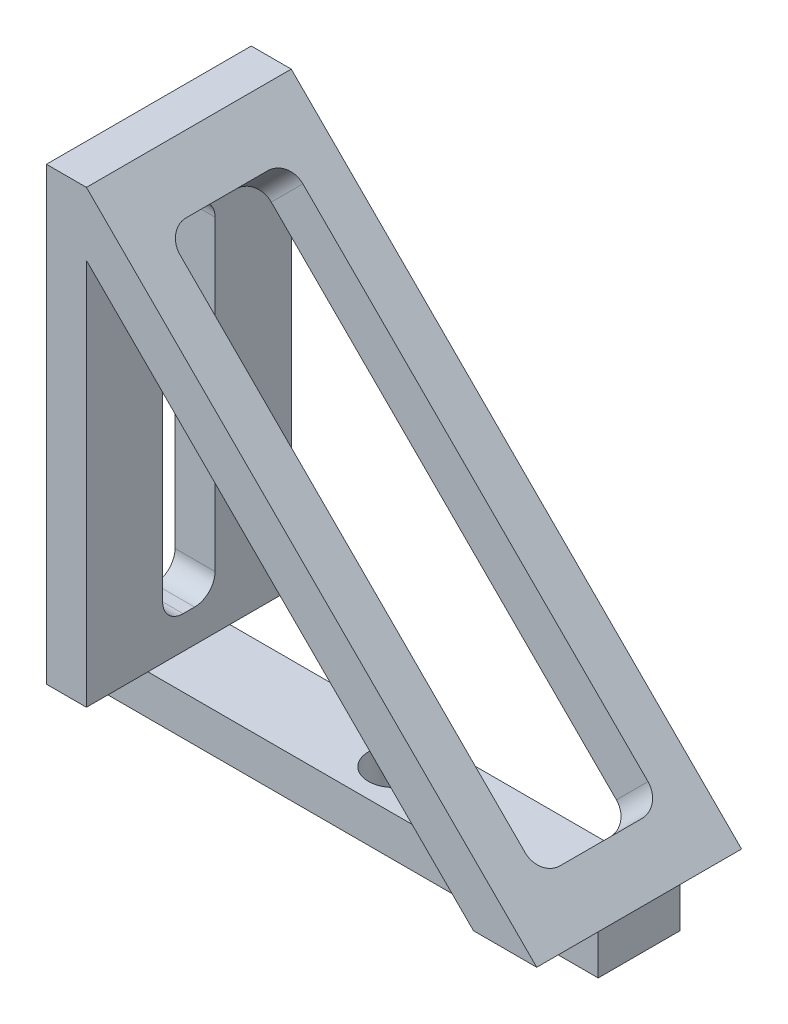
SolidWorks part; units mm, degrees
ref_plane "Front" through (0, 0, 0) normal (0, 0, 1) x (1, 0, 0)
ref_plane "Top" through (0, 0, 0) normal (0, 1, 0) x (1, 0, 0)
ref_plane "Right" through (0, 0, 0) normal (1, 0, 0) x (0, 0, -1)
sketch "Sketch1" plane through (0, 0, 0) normal (0, 0, 1) x (1, 0, 0)
  line L3 (-6.2, 69.8) -> (-6.2, -6.2)
  line L4 (-6.2, -6.2) -> (69.8, -6.2)
  line L6 (-6.2, 69.8) -> (0, 69.8)
  line L7 (0, 69.8) -> (69.8, 0)
  line L8 (50, 0) -> (-50, 0) construction
  line L9 (69.8, 0) -> (69.8, -6.2)
  line L10 (0, 60) -> (60, 0)
  line L11 (60, 0) -> (0, 0)
  line L12 (0, 0) -> (0, 60)
  dimension "D1" = 76
  dimension "D2" = 76
  dimension "D3" = 6.2
  dimension "D4" = 6.2
  dimension "D5" = 60
extrude "Boss-Extrude1" add sketch "Sketch1" along normal mid plane 31.75
sketch "Sketch2" plane through (34.9, 34.9, 0) normal (0.7071, 0.7071, 0) x (0, 0, -1)
  line L0 (0, 50) -> (0, -50) construction
  line L1 (-9.525, -41) -> (9.525, -41)
  line L2 (-9.525, -41) -> (-9.525, 41)
  line L3 (-9.525, 41) -> (9.525, 41)
  line L4 (9.525, -41) -> (9.525, 41)
  line L5 (-9.525, -41) -> (9.525, 41) construction
  line L6 (-9.525, 41) -> (9.525, -41) construction
  point P0 (0, 0)
  point P5 (9.525, 0)
  point P9 (0, 41)
  dimension "D1" = 82
  dimension "D2" = 19.05
extrude "Cut-Extrude1" cut sketch "Sketch2" against normal up to next
sketch "Sketch3" plane through (0, 0, 0) normal (1, 0, 0) x (0, 0, -1)
  line L0 (0, 50) -> (0, -50) construction
  line L1 (-4.064, 5.08) -> (4.064, 5.08)
  line L2 (-4.064, 5.08) -> (-4.064, 59)
  line L3 (-4.064, 59) -> (4.064, 59)
  line L4 (4.064, 5.08) -> (4.064, 59)
  line L5 (-4.064, 5.08) -> (4.064, 59) construction
  line L6 (-4.064, 59) -> (4.064, 5.08) construction
  line L7 (-15.875, 0) -> (15.875, 0) construction
  line L8 (-15.875, 60) -> (15.875, 60) construction
  point P0 (0, 32.04)
  point P5 (0, 59)
  point P12 (4.064, 59)
  dimension "D1" = 8.128
  dimension "D2" = 5.08
  dimension "D3" = 1
extrude "Cut-Extrude2" cut sketch "Sketch3" against normal up to next
sketch "Sketch4" plane through (69.8, 0, 0) normal (1, 0, 0) x (0, 0, -1)
  line L0 (50, 0) -> (-50, 0) construction
  line L1 (-15.875, -6.2) -> (-6.35, -6.2)
  line L2 (-15.875, -6.2) -> (-15.875, 0)
  line L3 (-15.875, 0) -> (-6.35, 0)
  line L4 (-6.35, -6.2) -> (-6.35, 0)
  line L6 (15.875, -6.2) -> (6.35, -6.2)
  line L7 (15.875, -6.2) -> (15.875, 0)
  line L8 (15.875, 0) -> (6.35, 0)
  line L9 (6.35, -6.2) -> (6.35, 0)
  dimension "D1" = 12.7
extrude "Cut-Extrude3" cut sketch "Sketch4" against normal up to next
sketch "Sketch5" plane through (0, -6.2, 0) normal (0, -1, 0) x (1, 0, 0)
  line L0 (50, 0) -> (-50, 0) construction
  line L1 (-6.2, 6.35) -> (69.8, 6.35) construction
  point P0 (31.8, 0)
  point P5 (31.8, 6.35)
hole_wizard "5/16 (0.3125) Diameter Hole1" positions "Sketch6" profile "Sketch8" hole size "5/16" standard "ANSI Inch" end condition through all
sketch "Sketch6" plane through (0, -6.2, 0) normal (0, -1, 0) x (-1, 0, 0)
  point P0 (-31.8, 0)
sketch "Sketch8" plane through (31.8, -6.2, 0) normal (1, 0, 0) x (0, 0, -1)
  line L0 (0, 0) -> (0, 76)
  line L1 (0, 76) -> (3.9687, 76)
  line L2 (3.9687, 76) -> (3.9687, 0)
  line L5 (3.9687, 0) -> (0, 0)
  line L11 (0, -6.35) -> (0, 107.95) construction
  dimension "Thru Hole Dia." = 7.9375
  dimension "Thru Hole Depth" = 76
fillet "Fillet1" radius 3.175 4 edges at (61.4414, 3.4586, 9.525) (61.4414, 3.4586, -9.525) (3.4586, 61.4414, -9.525) (3.4586, 61.4414, 9.525)
fillet "Fillet2" radius 3.175 4 edges at (-3.1, 5.08, 4.064) (-3.1, 5.08, -4.064) (-3.1, 59, 4.064) (-3.1, 59, -4.064)
ref_plane "Plane2" through (30, -30, 0) normal (-0.7071, 0.7071, 0) x (0, 0, 1)
ref_point "Point1"
ref_point "Point2"
